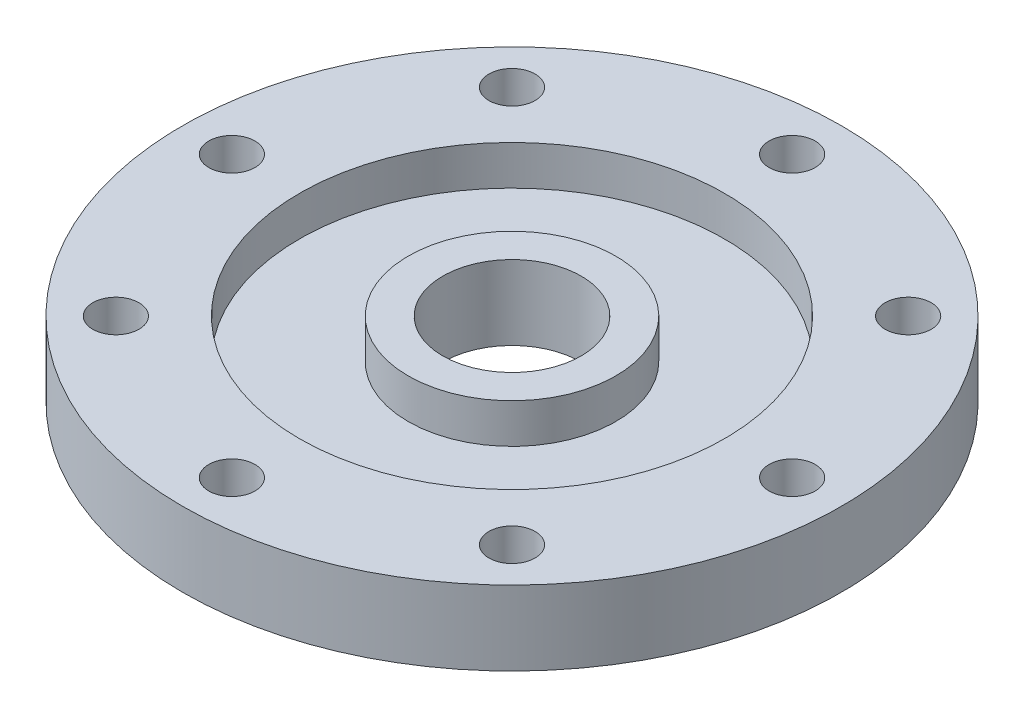
SolidWorks part; units mm, degrees
ref_plane "Front Plane" through (0, 0, 0) normal (0, 0, 1) x (1, 0, 0)
ref_plane "Top Plane" through (0, 0, 0) normal (0, 1, 0) x (1, 0, 0)
ref_plane "Right Plane" through (0, 0, 0) normal (1, 0, 0) x (0, 0, -1)
sketch "Sketch2" plane through (0, 0, 0) normal (0, 1, 0) x (1, 0, 0)
  circle A0 centre (0, 20.5533) radius 1.75 construction
  circle A1 centre (-15.026, 14.3294) radius 1.75 construction
  circle A2 centre (15.026, 14.3294) radius 1.75 construction
  circle A3 centre (-21.25, -0.6967) radius 1.75 construction
  circle A4 centre (21.25, 0) radius 1.75 construction
  circle A5 centre (-15.026, -15.7227) radius 1.75 construction
  circle A6 centre (0, -21.9467) radius 1.75 construction
  circle A7 centre (15.026, -15.7227) radius 1.75 construction
  circle A8 centre (0, 0) radius 5.25
  circle A9 centre (0, 0) radius 25
  circle A10 centre (0, 0) radius 21.25 construction
  circle A11 centre (0, 21.25) radius 1.75
  circle A12 centre (15.026, 15.026) radius 1.75
  circle A13 centre (21.25, 0) radius 1.75
  circle A14 centre (15.026, -15.026) radius 1.75
  circle A15 centre (0, -21.25) radius 1.75
  circle A16 centre (-15.026, -15.026) radius 1.75
  circle A17 centre (-21.25, 0) radius 1.75
  circle A18 centre (-15.026, 15.026) radius 1.75
  point P40 (0, 0)
  dimension "D1" = 42.5
  dimension "D2" = 50
  dimension "D3" = 10.5
  dimension "D4" = 3.5
  dimension "D5" = 8
extrude "Boss-Extrude1" add sketch "Sketch2" along normal mid plane 5.65
sketch "Sketch3" plane through (0, 2.825, 0) normal (0, 1, 0) x (1, 0, 0)
  circle A0 centre (0, 0) radius 16.125
  circle A1 centre (0, 0) radius 7.875
  dimension "D1" = 32.25
  dimension "D2" = 15.75
extrude "Cut-Extrude1" cut sketch "Sketch3" against normal blind 3
